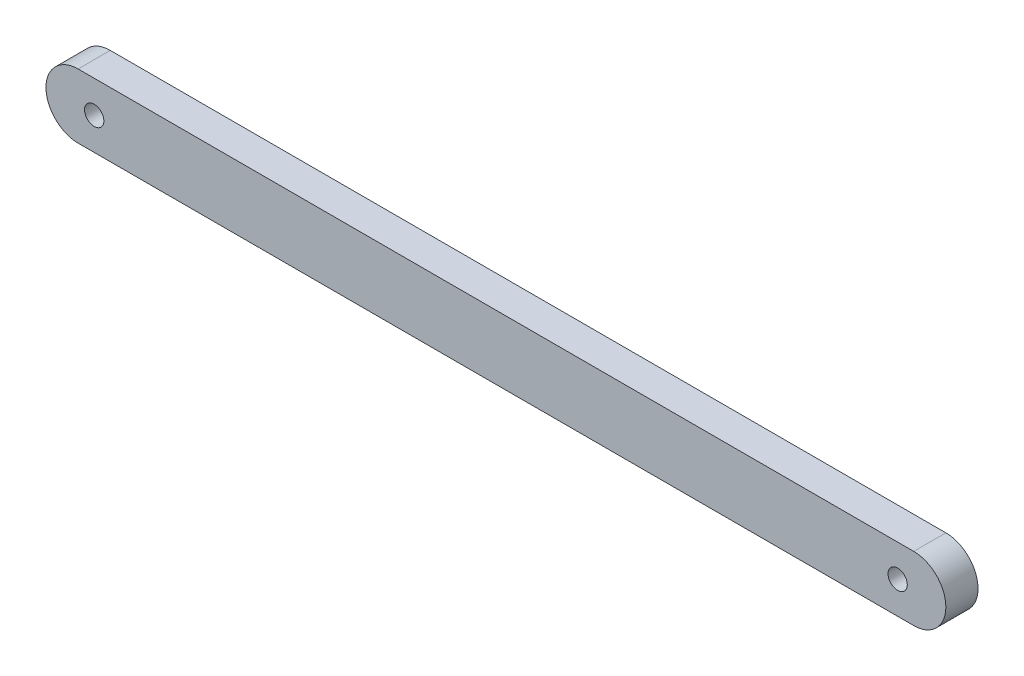
SolidWorks part; units mm, degrees
ref_plane "Plan de face" through (0, 0, 0) normal (0, 0, 1) x (1, 0, 0)
ref_plane "Plan de dessus" through (0, 0, 0) normal (0, 1, 0) x (1, 0, 0)
ref_plane "Plan de droite" through (0, 0, 0) normal (1, 0, 0) x (0, 0, -1)
sketch "Esquisse1" plane through (0, 0, 0) normal (0, 0, 1) x (1, 0, 0)
  line L1 (-122.6281, -8.2258) -> (137.3719, -8.2258)
  line L3 (-122.6281, -28.2258) -> (137.3719, -28.2258)
  circle A0 centre (-117.6281, -18.2258) radius 3
  circle A1 centre (132.3719, -18.2258) radius 3
  arc A2 (-122.6281, -28.2258) -> (-122.6281, -8.2258) centre (-122.6281, -18.2258) cw
  arc A3 (137.3719, -28.2258) -> (137.3719, -8.2258) centre (137.3719, -18.2258) ccw
  dimension "D2" = 6
  dimension "D3" = 6
  dimension "D5" = 10
  dimension "D1" = 250
  dimension "D4" = 20
  dimension "D6" = 5
  dimension "D7" = 5
extrude "Boss.-Extru.1" add sketch "Esquisse1" along normal blind 10
